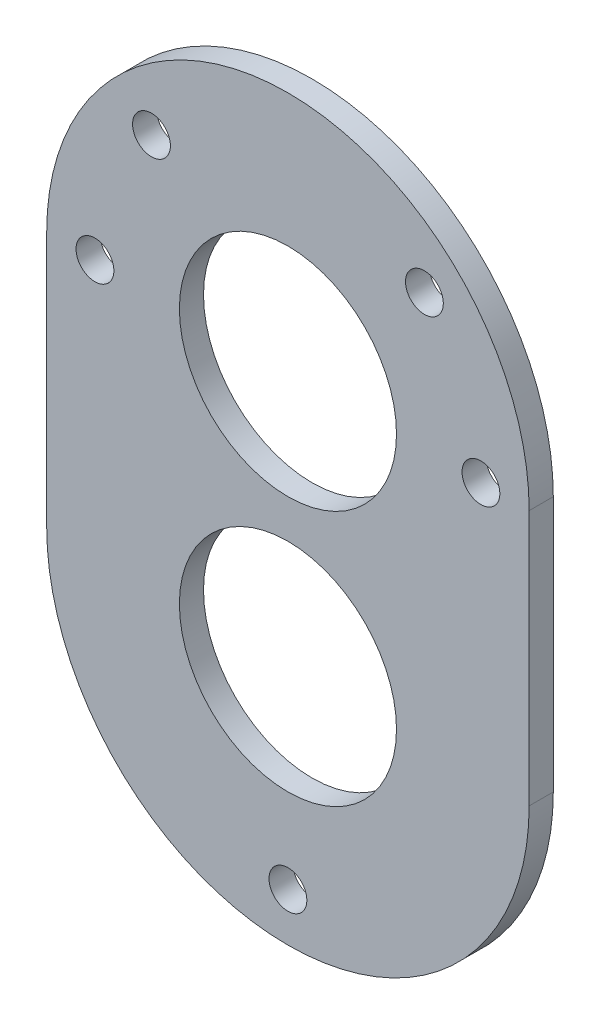
SolidWorks part; units mm, degrees
ref_plane "Front Plane" through (0, 0, 0) normal (1, 0, 0) x (0, 1, 0)
ref_plane "Top Plane" through (0, 0, 0) normal (0, 0, 1) x (0, 1, 0)
ref_plane "Right Plane" through (0, 0, 0) normal (0, 1, 0) x (-1, 0, 0)
sketch "Sketch1" plane through (0, 0, 0) normal (0, 0, 1) x (0, 1, 0)
  line L0 (-33.655, 31.75) -> (0, 31.75)
  line L1 (-33.655, -31.75) -> (0, -31.75)
  circle A0 centre (0, 0) radius 14.2875
  arc A1 (0, -31.75) -> (0, 31.75) centre (0, 0) ccw
  arc A2 (-33.655, 31.75) -> (-33.655, -31.75) centre (-33.655, 0) ccw
  circle A3 centre (-33.655, 0) radius 14.2875
  dimension "D1" = 28.575
  dimension "D2" = 63.5
  dimension "D3" = 63.5
  dimension "D4" = 28.575
  dimension "D5" = 33.655
extrude "Boss-Extrude1" add sketch "Sketch1" along normal blind 3.175
sketch "Sketch3" plane through (0, 0, 3.175) normal (0, 0, 1) x (1, 0, 0)
  circle A0 centre (0, 0) radius 25.4 construction
  circle A1 centre (0, -33.655) radius 25.4 construction
  circle A2 centre (0, -33.655) radius 14.2875 construction
  point P3 (-25.4, 0)
  point P5 (25.4, 0)
  point P10 (0, -59.055)
  point P16 (-17.9605, 17.9605)
  point P18 (17.9605, 17.9605)
  point P20 (-58.3859, 11.7737)
  dimension "D1" = 50.8
  dimension "D2" = 45
  dimension "D3" = 45
hole_wizard "#9 (0.196) Diameter Hole1" positions "Sketch3" profile "Sketch4" hole size "#9" standard "ANSI Inch" end condition through all
sketch "Sketch4" plane through (-58.3859, 11.7737, 3.175) normal (1, 0, 0) x (0, -1, 0)
  line L0 (0, 0) -> (0, 3.175)
  line L1 (0, 3.175) -> (2.4892, 3.175)
  line L2 (2.4892, 3.175) -> (2.4892, 0)
  line L5 (2.4892, 0) -> (0, 0)
  line L11 (0, -6.35) -> (0, 107.95) construction
  dimension "Thru Hole Dia." = 4.9784
  dimension "Thru Hole Depth" = 3.175
